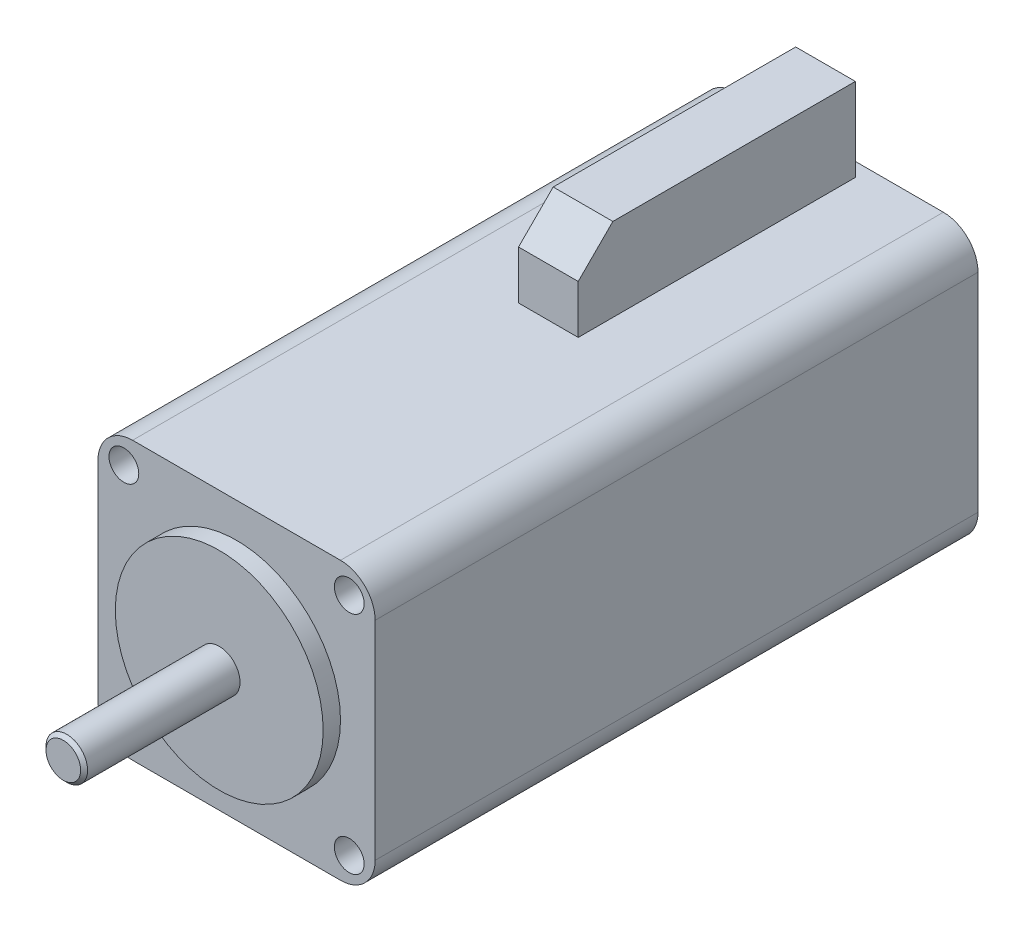
SolidWorks part; units mm, degrees
ref_plane "Front Plane" through (0, 0, 0) normal (0, 0, 1) x (1, 0, 0)
ref_plane "Top Plane" through (0, 0, 0) normal (0, 1, 0) x (1, 0, 0)
ref_plane "Right Plane" through (0, 0, 0) normal (1, 0, 0) x (0, 0, -1)
sketch "Sketch1" plane through (0, 0, 0) normal (0, 0, 1) x (1, 0, 0)
  line L1 (-20, 20) -> (20, 20)
  line L2 (-20, 20) -> (-20, -20)
  line L3 (-20, -20) -> (20, -20)
  line L4 (20, 20) -> (20, -20)
  line L5 (-20, 20) -> (20, -20) construction
  line L6 (-20, -20) -> (20, 20) construction
  point P0 (0, 0)
  dimension "D1" = 40
  dimension "D2" = 40
extrude "Boss-Extrude1" add sketch "Sketch1" along normal blind 5
fillet "Fillet1" radius 5 4 edges at (20, -20, 2.5) (-20, -20, 2.5) (-20, 20, 2.5) (20, 20, 2.5)
sketch "Sketch2" plane through (0, 0, 5) normal (0, 0, 1) x (1, 0, 0)
  circle A0 centre (0, 0) radius 15
  dimension "D1" = 30
  dimension "D2" = 0
extrude "Boss-Extrude2" add sketch "Sketch2" along normal blind 2.5
sketch "Sketch3" plane through (0, 0, 7.5) normal (0, 0, 1) x (1, 0, 0)
  circle A0 centre (0, 0) radius 3
  circle A1 centre (0, 0) radius 15 construction
  dimension "D1" = 6
  dimension "D2" = 0
extrude "Boss-Extrude3" add sketch "Sketch3" along normal blind 22.5
sketch "Sketch4" plane through (0, 0, 0) normal (0, 0, -1) x (-1, 0, 0)
  line L0 (-20, -15) -> (-20, 15) construction
  line L1 (-15, 20) -> (15, 20) construction
  line L2 (20, 15) -> (20, -15) construction
  line L3 (15, -20) -> (-15, -20) construction
  line L4 (-20, -15) -> (-20, 15)
  line L5 (-15, 20) -> (15, 20)
  line L6 (20, 15) -> (20, -15)
  line L7 (15, -20) -> (-15, -20)
  arc A0 (-15, 20) -> (-20, 15) centre (-15, 15) ccw construction
  arc A1 (20, 15) -> (15, 20) centre (15, 15) ccw construction
  arc A2 (15, -20) -> (20, -15) centre (15, -15) ccw construction
  arc A3 (-20, -15) -> (-15, -20) centre (-15, -15) ccw construction
  arc A4 (-15, 20) -> (-20, 15) centre (-15, 15) ccw
  arc A5 (20, 15) -> (15, 20) centre (15, 15) ccw
  arc A6 (15, -20) -> (20, -15) centre (15, -15) ccw
  arc A7 (-20, -15) -> (-15, -20) centre (-15, -15) ccw
  point P0 (0, 0)
  point P21 (5.1048, -3.9817)
extrude "Boss-Extrude5" add sketch "Sketch4" along normal blind 82
chamfer "Chamfer1" distance 0.5 angle 45 1 edges at (3, 0, 30)
sketch "Sketch5" plane through (0, 0, 5) normal (0, 0, 1) x (1, 0, 0)
  line L1 (-18.5355, 18.5355) -> (18.5355, -18.5355) construction
  circle A0 centre (-16.2635, 16.2635) radius 2.15
  arc A2 (-15, 20) -> (-20, 15) centre (-15, 15) ccw construction
  arc A3 (15, -20) -> (20, -15) centre (15, -15) ccw construction
  circle A4 centre (16.2635, 16.2635) radius 2.15
  circle A5 centre (16.2635, -16.2635) radius 2.15
  circle A6 centre (-16.2635, -16.2635) radius 2.15
  point P20 (0, 0)
  dimension "D1" = 4.3
  dimension "D2" = 4
  dimension "D3" = 23
extrude "Cut-Extrude1" cut sketch "Sketch5" against normal blind 10
sketch "Sketch6" plane through (0, 20, 0) normal (0, 1, 0) x (1, 0, 0)
  line L0 (-15, 82) -> (15, 82) construction
  line L1 (-4.3056, 80) -> (4.3056, 80)
  line L2 (-4.3056, 80) -> (-4.3056, 40)
  line L3 (-4.3056, 40) -> (4.3056, 40)
  line L4 (4.3056, 80) -> (4.3056, 40)
  line L5 (-4.3056, 80) -> (4.3056, 40) construction
  line L6 (-4.3056, 40) -> (4.3056, 80) construction
  point P0 (0, 60)
  dimension "D1" = 22
  dimension "D2" = 40
extrude "Boss-Extrude6" add sketch "Sketch6" along normal blind 12
chamfer "Chamfer2" distance 5 angle 45 1 edges at (0, 32, -40)
